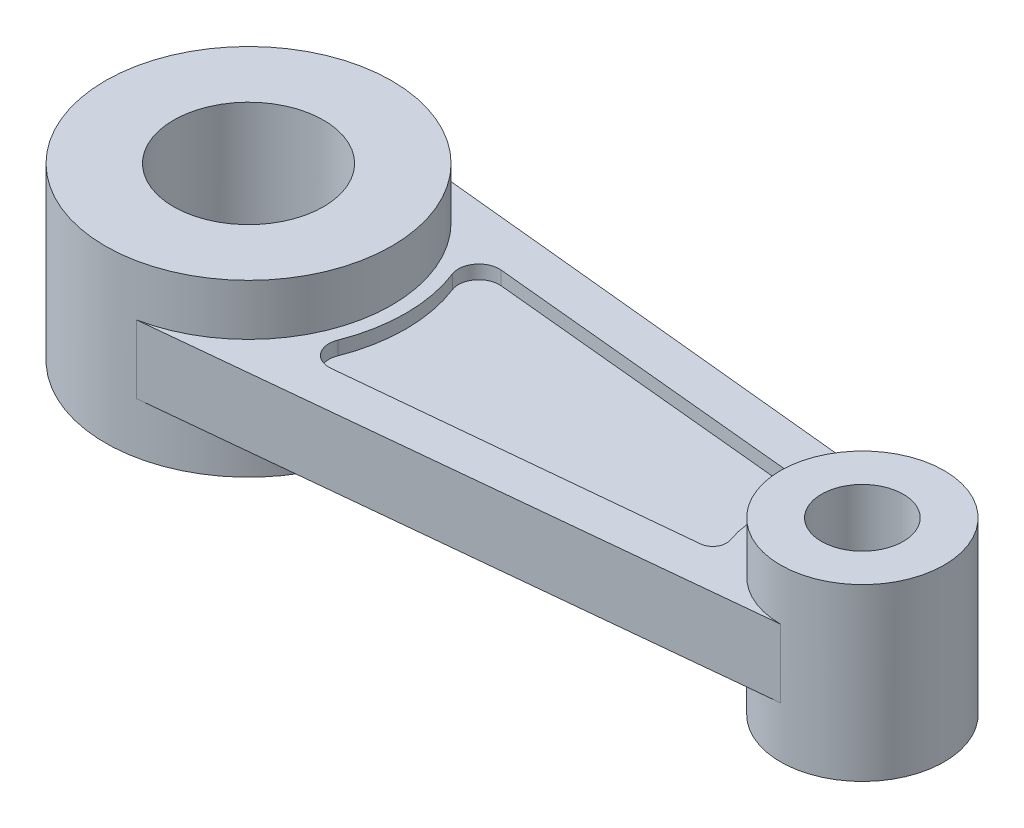
SolidWorks part; units mm, degrees
ref_plane "Front Plane" through (0, 0, 0) normal (0, 0, 1) x (1, 0, 0)
ref_plane "Top Plane" through (0, 0, 0) normal (0, 1, 0) x (1, 0, 0)
ref_plane "Right Plane" through (0, 0, 0) normal (1, 0, 0) x (0, 0, -1)
sketch "Sketch1" plane through (0, 0, 0) normal (0, 1, 0) x (1, 0, 0)
  line L0 (0, 0) -> (90, 0) construction
  line L1 (90, -12) -> (0, -21)
  line L2 (0, 21) -> (90, 12)
  line L3 (0, 21) -> (0, -21)
  line L4 (90, 12) -> (90, -12)
  dimension "D1" = 90
  dimension "D3" = 12
  dimension "D2" = 90
  dimension "D4" = 21
extrude "Boss-Extrude1" add sketch "Sketch1" along normal mid plane 10 contours L2 L4 L1 L3
sketch "Sketch2" plane through (0, 5, 0) normal (0, 1, 0) x (1, 0, 0)
  circle A0 centre (0, 0) radius 21
extrude "Boss-Extrude3" add sketch "Sketch2" along normal mid plane 15 contours A0
sketch "Sketch3" plane through (0, 5, 0) normal (0, 1, 0) x (1, 0, 0)
  line L0 (90, 12) -> (90, -12) construction
  circle A0 centre (90, 0) radius 12
extrude "Boss-Extrude4" add sketch "Sketch3" along normal mid plane 15 contours A0
sketch "Sketch4" plane through (0, -5, 0) normal (0, -1, 0) x (1, 0, 0)
  circle A0 centre (0, 0) radius 21
extrude "Boss-Extrude6" add sketch "Sketch4" along normal mid plane 15 contours A0
sketch "Sketch5" plane through (0, -5, 0) normal (0, -1, 0) x (1, 0, 0)
  line L0 (90, -12) -> (90, 12) construction
  circle A0 centre (90, 0) radius 12
extrude "Boss-Extrude7" add sketch "Sketch5" along normal mid plane 15 contours A0
sketch "Sketch6" plane through (0, 12.5, 0) normal (0, 1, 0) x (1, 0, 0)
  circle A0 centre (0, 0) radius 11
  dimension "D1" = 22
extrude "Cut-Extrude1" cut sketch "Sketch6" against normal blind 69 contours A0
sketch "Sketch7" plane through (0, 12.5, 0) normal (0, 1, 0) x (1, 0, 0)
  circle A0 centre (90, 0) radius 6
  dimension "D1" = 12
extrude "Cut-Extrude2" cut sketch "Sketch7" against normal blind 69 contours A0
sketch "Sketch8" plane through (0, 5, 0) normal (0, 1, 0) x (1, 0, 0)
  line L0 (24.5627, 12.4774) -> (73.9432, 7.6773)
  line L1 (24.5627, -12.4774) -> (73.9432, -7.6773)
  arc A0 (21.4785, -8.3989) -> (21.4785, 8.3989) centre (0, 0) ccw
  arc A1 (75.6375, 5.0261) -> (75.6375, -5.0261) centre (90, 0) ccw
  arc A2 (75.6375, 5.0261) -> (73.9432, 7.6773) centre (73.7497, 5.6867) ccw
  arc A3 (73.9432, -7.6773) -> (75.6375, -5.0261) centre (73.7497, -5.6867) ccw
  arc A4 (24.5627, -12.4774) -> (21.4785, -8.3989) centre (24.2724, -9.4915) cw
  arc A5 (21.4785, 8.3989) -> (24.5627, 12.4774) centre (24.2724, 9.4915) cw
  point P1 (76.7088, 7.4085)
  point P5 (19.0393, 13.0143)
  point P6 (19.0393, -13.0143)
  dimension "D1" = 2
  dimension "D2" = 2
  dimension "D3" = 3
  dimension "D4" = 3
extrude "Cut-Extrude4" cut sketch "Sketch8" against normal blind 2 contours L1 A3 A1 A2 L0 A5 A0 A4
sketch "Sketch9" plane through (0, -5, 0) normal (0, -1, 0) x (1, 0, 0)
  line L0 (75.6539, 8.1177) -> (25.3522, 12.9519)
  line L1 (25.3522, -12.9519) -> (75.6539, -8.1177)
  arc A4 (22.2775, -8.8573) -> (22.2775, 8.8573) centre (0, 0) ccw
  arc A5 (77.3055, 5.3502) -> (77.3055, -5.3502) centre (90, 0) ccw
  arc A6 (22.2775, 8.8573) -> (25.3522, 12.9519) centre (25.0652, 9.9657) cw
  arc A7 (25.3522, -12.9519) -> (22.2775, -8.8573) centre (25.0652, -9.9657) cw
  arc A8 (77.3055, 5.3502) -> (75.6539, 8.1177) centre (75.4625, 6.1269) ccw
  arc A9 (75.6539, -8.1177) -> (77.3055, -5.3502) centre (75.4625, -6.1269) ccw
  dimension "D1" = 3
  dimension "D2" = 3
  dimension "D3" = 2
  dimension "D4" = 2
extrude "Cut-Extrude5" cut sketch "Sketch9" against normal blind 2 contours L0 A6 A4 A7 L1 A9 A5 A8
